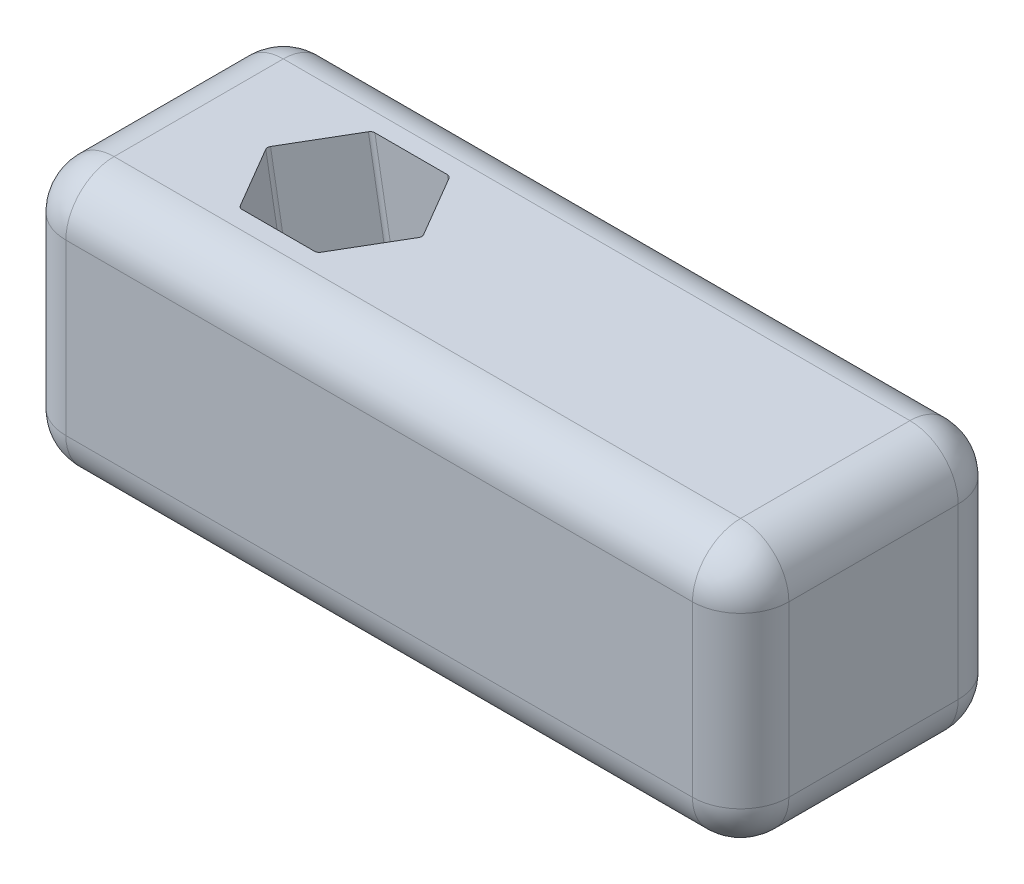
SolidWorks part; units mm, degrees
ref_plane "Front Plane" through (0, 0, 0) normal (0, 0, 1) x (1, 0, 0)
ref_plane "Top Plane" through (0, 0, 0) normal (0, 1, 0) x (1, 0, 0)
ref_plane "Right Plane" through (0, 0, 0) normal (1, 0, 0) x (0, 0, -1)
sketch "Sketch1" plane through (0, 0, 0) normal (0, 0, 1) x (1, 0, 0)
  line L1 (0, 0) -> (38.1, 0)
  line L2 (0, 0) -> (0, 14)
  line L3 (0, 14) -> (38.1, 14)
  line L4 (38.1, 0) -> (38.1, 14)
  dimension "D1" = 14
  dimension "D2" = 38.1
extrude "Boss-Extrude1" add sketch "Sketch1" along normal mid plane 14
fillet "Fillet1" radius 2.54 12 edges at (19.05, 0, -7) (38.1, 7, -7) (19.05, 14, -7) (0, 7, -7) (19.05, 14, 7) (38.1, 7, 7) (19.05, 0, 7) (0, 7, 7) (0, 0, 0) (0, 14, 0) (38.1, 0, 0) (38.1, 14, 0)
sketch "Sketch2" plane through (0, 0, 0) normal (0, 0, 1) x (1, 0, 0)
  line L0 (0, 0) -> (12.7, 0) construction
  line L1 (12.7, 0) -> (-11.5175, 137.3443) construction
  dimension "D1" = 80
  dimension "D2" = 12.7
ref_plane "Plane1" through (-2.3176, 13.1435, 0) normal (-0.1736, 0.9848, 0) x (0.9848, 0.1736, 0)
sketch "Sketch3" plane through (-2.3176, 13.1435, 0) normal (-0.1736, 0.9848, 0) x (0.9848, 0.1736, 0)
  line L1 (16.5485, 0) -> (14.5278, 3.5)
  line L2 (14.5278, 3.5) -> (10.4863, 3.5)
  line L3 (10.4863, 3.5) -> (8.4656, 0)
  line L4 (8.4656, 0) -> (10.4863, -3.5)
  line L5 (10.4863, -3.5) -> (14.5278, -3.5)
  line L6 (14.5278, -3.5) -> (16.5485, 0)
  circle A0 centre (12.5071, 0) radius 3.5 construction
  dimension "D1" = 7
extrude "Cut-Extrude1" cut sketch "Sketch3" against normal blind 12.7
fillet "Fillet2" radius 1 6 edges at (12.2048, 2.8083, 3.5) (9.2198, 2.2819, 1.75) (9.2198, 2.2819, -1.75) (12.2048, 2.8083, -3.5) (15.1899, 3.3346, -1.75) (15.1899, 3.3346, 1.75)
fillet "Fillet3" radius 0.25 12 edges at (13.9775, 3.4182, 3.2071) (8.507, 2.4536, 0) (10.3305, 2.7752, 3.2071) (15.801, 3.7398, 0) (13.9775, 3.4182, -3.2071) (10.3305, 2.7752, -3.2071) (13.1523, 9.072, 3.5) (7.0894, 8.5456, 0) (9.1103, 8.7211, 3.5) (15.1732, 9.2474, 0) (13.1523, 9.072, -3.5) (9.1103, 8.7211, -3.5)
